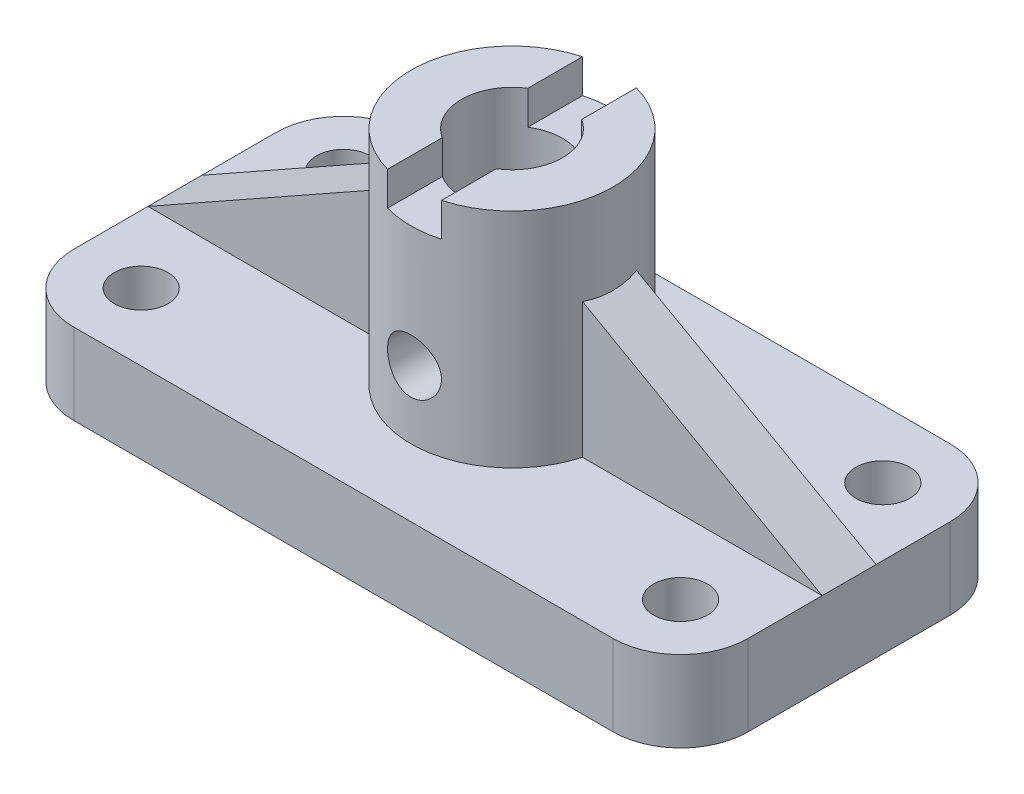
SolidWorks part; units mm, degrees
ref_plane "前视基准面" through (0, 0, 0) normal (0, 0, 1) x (1, 0, 0)
ref_plane "上视基准面" through (0, 0, 0) normal (0, 1, 0) x (1, 0, 0)
ref_plane "右视基准面" through (0, 0, 0) normal (1, 0, 0) x (0, 0, -1)
other "Configuration Table"
sketch "草图1" plane through (0, 0, 0) normal (0, 1, 0) x (1, 0, 0)
  line L0 (0, 0) -> (0, 25) construction
  line L1 (50, 25) -> (-50, 25)
  line L2 (50, 25) -> (50, -25)
  line L3 (50, -25) -> (-50, -25)
  line L4 (-50, 25) -> (-50, -25)
  line L5 (50, 25) -> (-50, -25) construction
  line L6 (50, -25) -> (-50, 25) construction
  line L7 (0, 0) -> (-50, 0) construction
  circle A0 centre (-40, 15) radius 4
  circle A1 centre (-40, -15) radius 4
  circle A2 centre (40, -15) radius 4
  circle A3 centre (40, 15) radius 4
  point P0 (0, 0)
  dimension "D5" = 8
  dimension "D1" = 10
  dimension "D2" = 10
  dimension "D3" = 50
  dimension "D4" = 100
extrude "凸台-拉伸1" add sketch "草图1" along normal blind 12
fillet "圆角1" radius 10 1 edges at (50, 6, -25)
fillet "圆角2" radius 10 3 edges at (50, 6, 25) (-50, 6, 25) (-50, 6, -25)
sketch "草图2" plane through (0, 12, 0) normal (0, 1, 0) x (1, 0, 0)
  circle A0 centre (0, 0) radius 15
  dimension "D1" = 30
extrude "凸台-拉伸2" add sketch "草图2" along normal blind 33
sketch "草图3" plane through (0, 45, 0) normal (0, 1, 0) x (1, 0, 0)
  circle A0 centre (0, 0) radius 7.5
  circle A1 centre (0, 0) radius 15
  circle A2 centre (0, 0) radius 15
  dimension "D1" = 0
  dimension "D2" = 7.5
extrude "切除-拉伸1" cut sketch "草图3" against normal through all contours A0
ref_plane "基准面1" through (0, 55, 0) normal (0, 1, 0) x (1, 0, 0)
sketch "草图4" plane through (0, 55, 0) normal (0, 1, 0) x (1, 0, 0)
  line L1 (4, -22.5) -> (-4, -22.5)
  line L2 (4, -22.5) -> (4, 22.5)
  line L3 (4, 22.5) -> (-4, 22.5)
  line L4 (-4, -22.5) -> (-4, 22.5)
  line L5 (4, -22.5) -> (-4, 22.5) construction
  line L6 (4, 22.5) -> (-4, -22.5) construction
  point P0 (0, 0)
  dimension "D1" = 8
  dimension "D2" = 45
extrude "切除-拉伸2" cut sketch "草图4" against normal blind 5 from surface at -10 starting at face at (0, 45, 7.5)
ref_plane "基准面2" through (0, 0, 15) normal (0, 0, 1) x (1, 0, 0)
sketch "草图5" plane through (0, 0, 15) normal (0, 0, 1) x (1, 0, 0)
  line L0 (-40, 12) -> (40, 12) construction
  line L1 (-40, 12) -> (40, 12)
  circle A0 centre (0, 22) radius 4
  dimension "D1" = 8
  dimension "D2" = 10
extrude "切除-拉伸3" cut sketch "草图5" against normal through all both and the other way through all contours A0
sketch "草图6" plane through (0, 12, 0) normal (0, 1, 0) x (1, 0, 0)
  line L0 (-50, 15) -> (-50, -15) construction
  line L1 (50, -4) -> (-50, -4)
  line L2 (50, -4) -> (50, 4)
  line L3 (50, 4) -> (-50, 4)
  line L4 (-50, -4) -> (-50, 4)
  line L5 (50, -4) -> (-50, 4) construction
  line L6 (50, 4) -> (-50, -4) construction
  line L8 (-14.4568, 4) -> (-14.4568, -4) construction
  arc A1 (-4, 14.4568) -> (-4, -14.4568) centre (0, 0) ccw construction
  point P0 (0, 0)
  point P8 (0, 0)
  dimension "D1" = 8
ref_plane "基准面4" through (0, 0, 4) normal (0, 0, 1) x (1, 0, 0)
sketch "草图8" plane through (0, 0, 4) normal (0, 0, 1) x (1, 0, 0)
  line L0 (-50, 12) -> (-14.4568, 12)
  line L1 (-14.4568, 12) -> (-14.4568, 32)
  line L2 (-14.4568, 32) -> (-50, 12)
  point P0 (-50, 12)
  point P2 (-14.4568, 12)
  dimension "D1" = 20
extrude "凸台-拉伸3" add sketch "草图8" against normal blind 8
mirror "镜向1" about plane through (0, 0, 0) normal (1, 0, 0) of "凸台-拉伸3"
